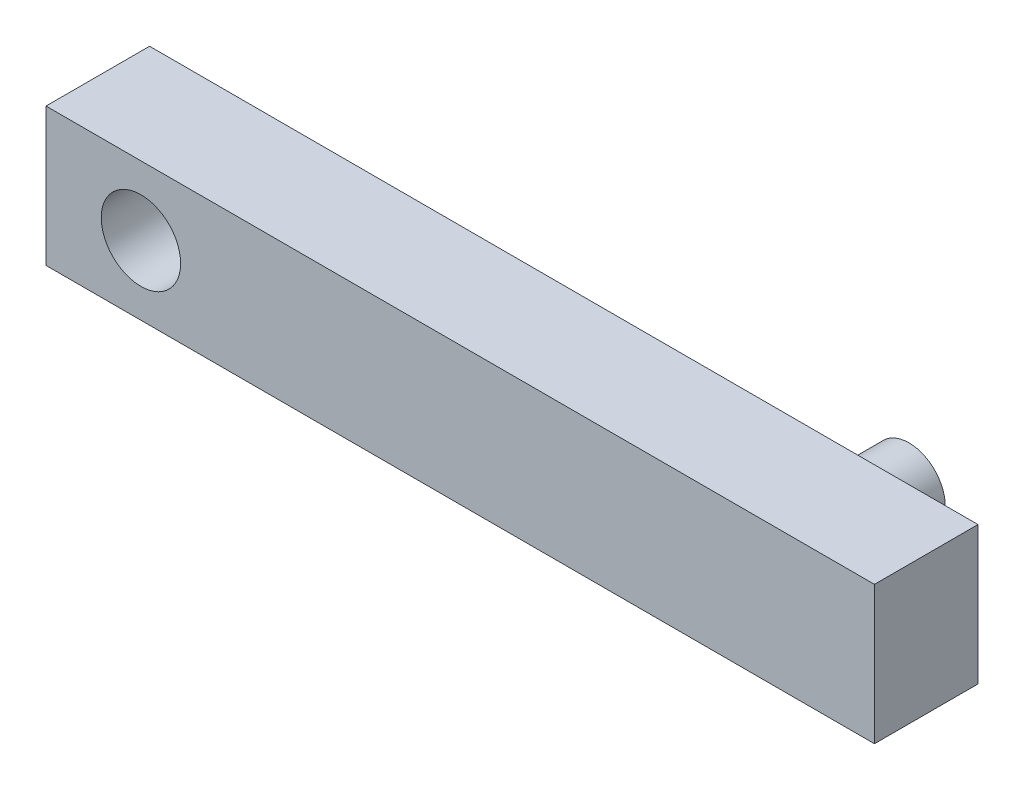
SolidWorks part; units mm, degrees
ref_plane "Alzado" through (0, 0, 0) normal (0, 0, 1) x (1, 0, 0)
ref_plane "Planta" through (0, 0, 0) normal (0, 1, 0) x (1, 0, 0)
ref_plane "Vista lateral" through (0, 0, 0) normal (1, 0, 0) x (0, 0, -1)
sketch "Croquis1" plane through (0, 0, 0) normal (0, 0, 1) x (1, 0, 0)
  line L1 (0, 0) -> (24, 0)
  line L2 (0, 0) -> (0, -4)
  line L3 (0, -4) -> (24, -4)
  line L4 (24, 0) -> (24, -4)
  circle A0 centre (4, -2) radius 1
  dimension "D5" = 2
  dimension "D1" = 4
  dimension "D2" = 24
  dimension "D3" = 20
  dimension "D4" = 2
extrude "Saliente-Extruir1" add sketch "Croquis1" along normal blind 3 contours L1 L4 L3 L2
sketch "Croquis3" plane through (0, 0, 0) normal (0, 0, -1) x (-1, 0, 0)
  line L0 (0, 0) -> (0, -4) construction
  line L1 (0, 0) -> (-24, 0) construction
  circle A0 centre (-20, -2) radius 1.05
  dimension "D3" = 2.1
  dimension "D1" = 20
  dimension "D2" = 2
sketch "Croquis4" plane through (0, 0, 3) normal (0, 0, 1) x (1, 0, 0)
  line L0 (0, 0) -> (24, 0) construction
  circle A0 centre (2.75, -2) radius 1.15
  dimension "D2" = 2.3
  dimension "D3" = 2
extrude "Cortar-Extruir2" cut sketch "Croquis4" against normal through all
extrude "Saliente-Extruir3" add sketch "Croquis3" along normal blind 2
